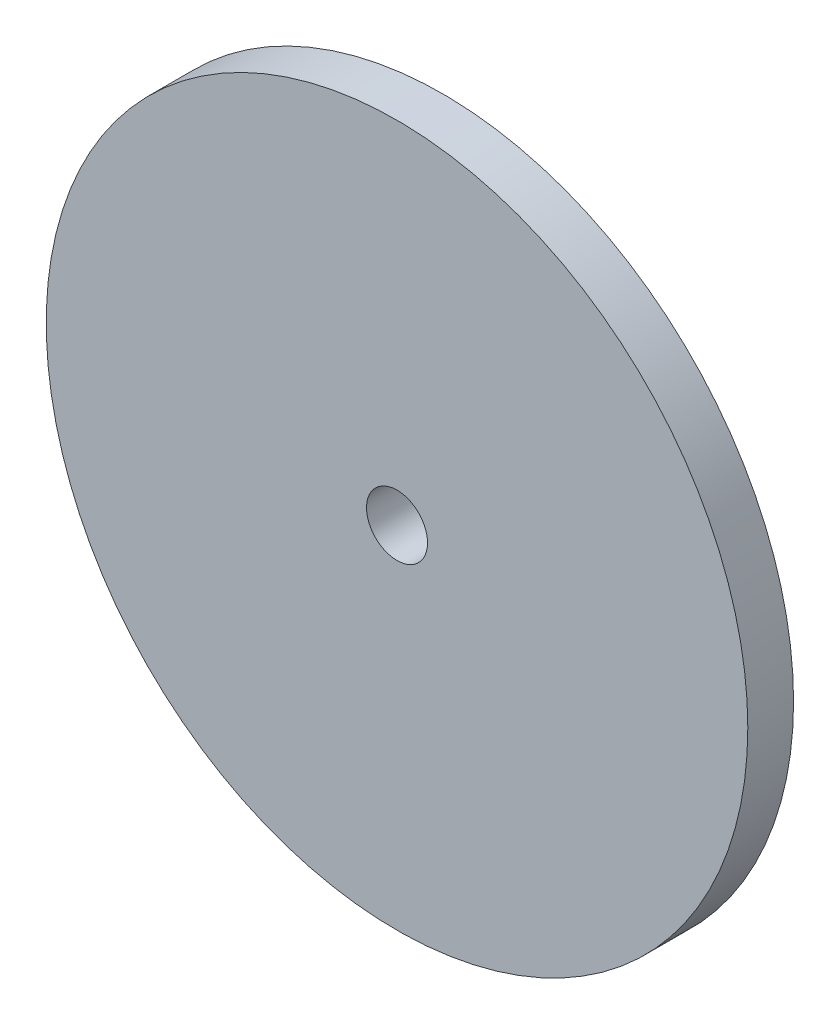
SolidWorks part; units mm, degrees
material "ABS"
ref_plane "Front Plane" through (0, 0, 0) normal (0, 0, 1) x (1, 0, 0)
ref_plane "Top Plane" through (0, 0, 0) normal (0, 1, 0) x (1, 0, 0)
ref_plane "Right Plane" through (0, 0, 0) normal (1, 0, 0) x (0, 0, -1)
sketch "Sketch1" plane through (0, 0, 0) normal (0, 1, 0) x (1, 0, 0)
  line L0 (0, 0) -> (0, 9.627) construction
  line L1 (1, 0) -> (1, 6)
  line L2 (1, 6) -> (2.4, 6)
  line L3 (2.4, 6) -> (2.4, 1.5)
  line L4 (2.4, 1.5) -> (11.5, 1.5)
  line L5 (11.5, 1.5) -> (11.5, 0)
  line L6 (11.5, 0) -> (1, 0)
  dimension "D1" = 6
  dimension "D2" = 1.5
  dimension "D3" = 1
  dimension "D4" = 11.5
  dimension "D5" = 2.4
revolve "Revolve1" add sketch "Sketch1" angle 360 about L0
